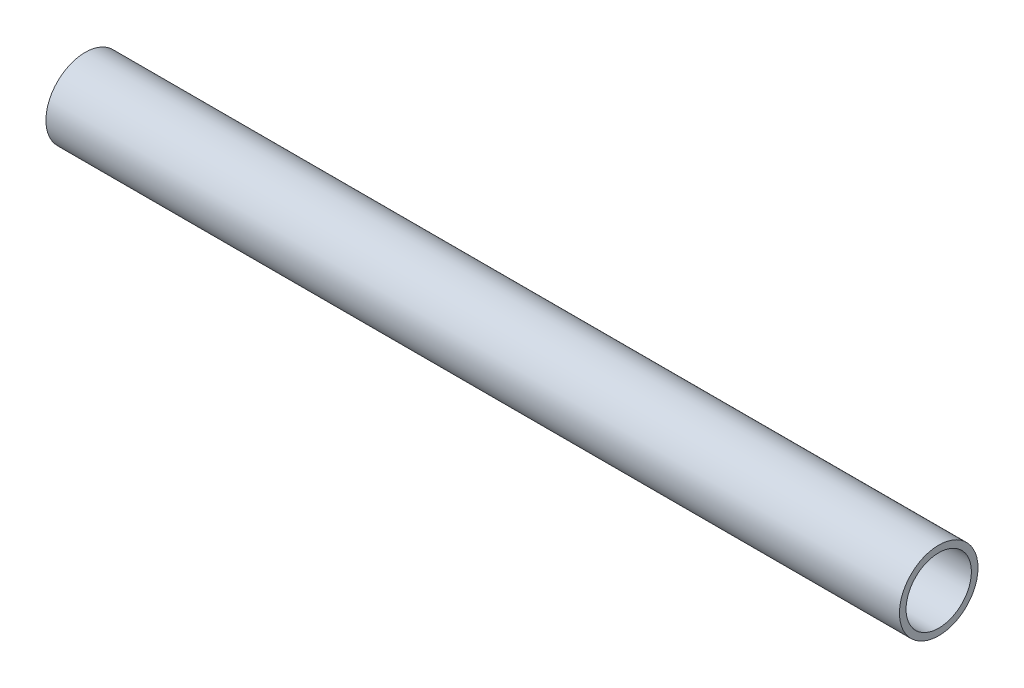
SolidWorks part; units mm, degrees
ref_plane "Front Plane" through (0, 0, 0) normal (0, 0, 1) x (1, 0, 0)
ref_plane "Top Plane" through (0, 0, 0) normal (0, 1, 0) x (1, 0, 0)
ref_plane "Right Plane" through (0, 0, 0) normal (1, 0, 0) x (0, 0, -1)
sketch "Sketch1" plane through (0, 0, 0) normal (0, 0, 1) x (1, 0, 0)
  line L0 (-106.534, 1471.8597) -> (31.4792, 1471.8597)
  point P2 (-106.534, 1471.8597)
  point P3 (31.4792, 1471.8597)
other "Pipe 0.5 SCH 40(1)"
ref_plane "Plane1" through (-106.534, 1471.8597, 0) normal (1, 0, 0) x (0, 1, 0)
sketch "Sketch11" plane through (-106.534, 1471.8597, 0) normal (1, 0, 0) x (0, 1, 0)
  circle A0 centre (0, 0) radius 5.2832
  circle A1 centre (0, 0) radius 6.35
  point P5 (0, 0)
  dimension "D1" = 12.7
  dimension "D2" = 10.5664
